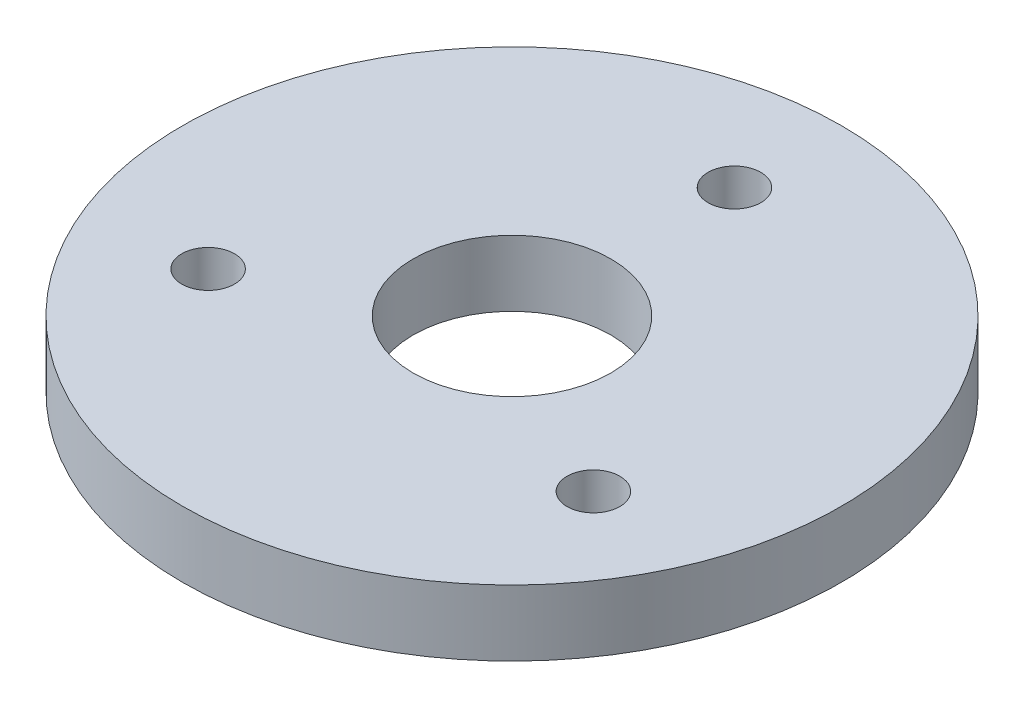
SolidWorks part; units mm, degrees
material "黑玻纤板"
ref_plane "前视基准面" through (0, 0, 0) normal (0, 0, 1) x (1, 0, 0)
ref_plane "上视基准面" through (0, 0, 0) normal (0, 1, 0) x (1, 0, 0)
ref_plane "右视基准面" through (0, 0, 0) normal (1, 0, 0) x (0, 0, -1)
sketch "草图1" plane through (0, 0, 0) normal (0, 1, 0) x (1, 0, 0)
  circle A46 centre (0, 0) radius 13.5 construction
  circle A47 centre (0, 13.5) radius 1.6
  circle A48 centre (11.6913, -6.75) radius 1.6
  circle A49 centre (-11.6913, -6.75) radius 1.6
  circle A50 centre (0, 0) radius 20
  circle A51 centre (0, 0) radius 6
  point P10 (0, 0)
  dimension "D1" = 27
  dimension "D2" = 3
  dimension "D3" = 3.2
  dimension "D4" = 40
  dimension "D5" = 12
extrude "凸台-拉伸1" add sketch "草图1" along normal blind 4
